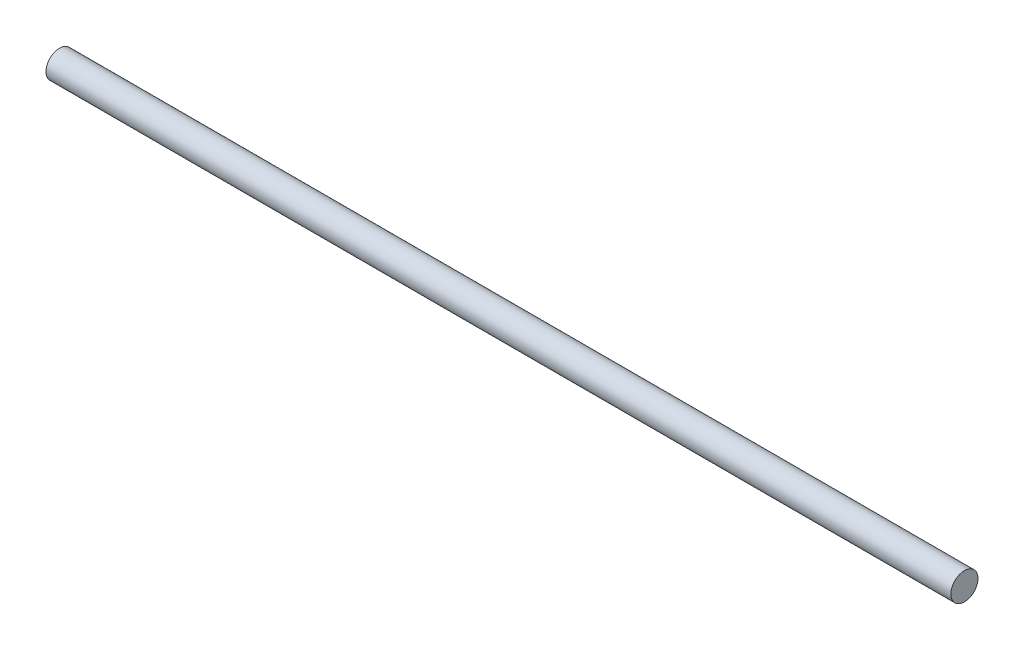
SolidWorks part; units mm, degrees
material "Zoltek Panex 33"
ref_plane "Front Plane" through (0, 0, 0) normal (0, 0, 1) x (1, 0, 0)
ref_plane "Top Plane" through (0, 0, 0) normal (0, 1, 0) x (1, 0, 0)
ref_plane "Right Plane" through (0, 0, 0) normal (1, 0, 0) x (0, 0, -1)
sketch "Sketch1" plane through (0, 0, 0) normal (1, 0, 0) x (0, 0, -1)
  circle A0 centre (0, 0) radius 9
  dimension "D1" = 18
extrude "Boss-Extrude1" add sketch "Sketch1" along normal mid plane 600
